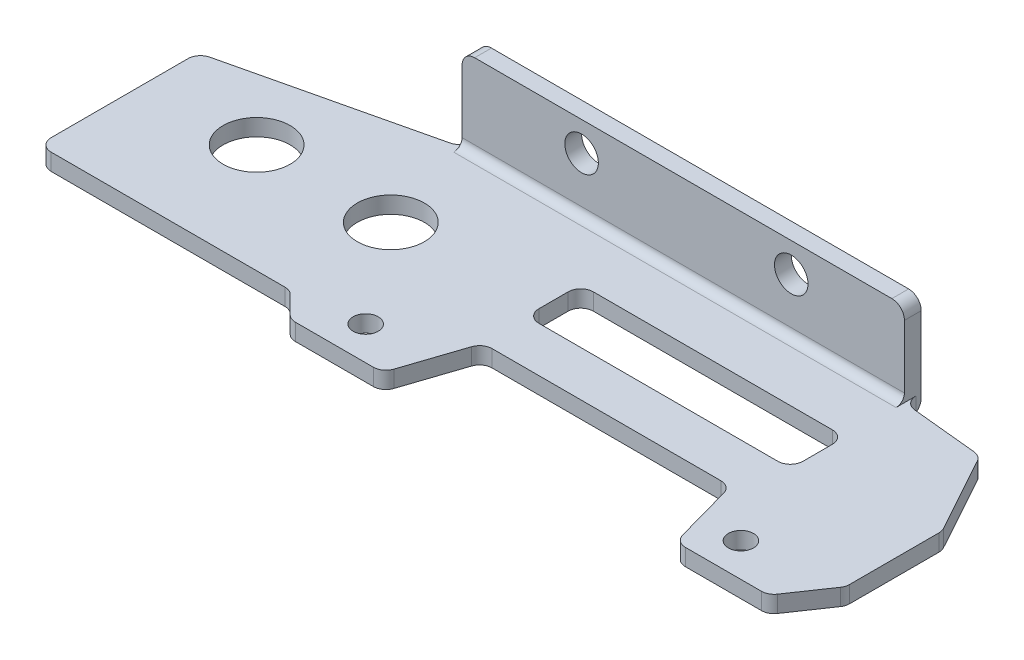
SolidWorks part; units mm, degrees
material "1060 Alloy"
ref_plane "Front Plane" through (0, 0, 0) normal (0, 0, 1) x (1, 0, 0)
ref_plane "Top Plane" through (0, 0, 0) normal (0, 1, 0) x (1, 0, 0)
ref_plane "Right Plane" through (0, 0, 0) normal (1, 0, 0) x (0, 0, -1)
sketch "Sketch1" plane through (0, 0, 0) normal (0, 1, 0) x (1, 0, 0)
  line L0 (0, 5.6) -> (30, 5.6)
  line L1 (33, 2.6) -> (44, 2.6)
  line L2 (0, 5.6) -> (0, 24.6)
  line L3 (25.5, 32.6) -> (78.25, 32.6)
  line L4 (93.75, 8.1) -> (93.75, 19.6)
  line L5 (30, 5.6) -> (33, 2.6)
  line L6 (0, 24.6) -> (25.5, 30.6)
  line L7 (25.5, 30.6) -> (25.5, 32.6)
  line L8 (78.25, 32.6) -> (78.25, 30.6)
  line L9 (78.25, 30.6) -> (88.25, 29.6)
  line L10 (88.25, 29.6) -> (93.75, 19.6)
  line L11 (93.75, 8.1) -> (90, 2.6)
  line L12 (44, 2.6) -> (47, 11.6)
  line L13 (47, 11.6) -> (76.5, 11.6)
  line L14 (76.5, 11.6) -> (79, 2.6)
  line L15 (79, 2.6) -> (90, 2.6)
  line L17 (46.75, 23.5) -> (78.25, 23.5)
  line L18 (46.75, 23.5) -> (46.75, 17)
  line L19 (46.75, 17) -> (78.25, 17)
  line L20 (78.25, 23.5) -> (78.25, 17)
  circle A0 centre (82.75, 6.6) radius 1.5
  circle A1 centre (38, 6.6) radius 1.5
  circle A2 centre (13, 18.6) radius 4
  circle A3 centre (29, 18.6) radius 4
  dimension "D20" = 3
  dimension "D21" = 4
  dimension "D22" = 11
  dimension "D23" = 38
  dimension "D24" = 3
  dimension "D25" = 8
  dimension "D26" = 13
  dimension "D27" = 16
  dimension "D28" = 13
  dimension "D1" = 52.75
  dimension "D2" = 10
  dimension "D3" = 3
  dimension "D4" = 3
  dimension "D5" = 2
  dimension "D6" = 25.5
  dimension "D7" = 8
  dimension "D8" = 3
  dimension "D9" = 10
  dimension "D10" = 5.5
  dimension "D11" = 3.75
  dimension "D12" = 5.5
  dimension "D13" = 29.5
  dimension "D14" = 11
  dimension "D15" = 9
  dimension "D16" = 3
  dimension "D17" = 11
  dimension "D18" = 30
  dimension "D19" = 19
  dimension "D29" = 6.5
  dimension "D30" = 31.5
  dimension "D31" = 15.5
  dimension "D32" = 5.4
  dimension "D33" = 2
extrude "Boss-Extrude1" add sketch "Sketch1" along normal blind 2
sketch "Sketch2" plane through (0, 2, 0) normal (0, 1, 0) x (1, 0, 0)
  line L1 (25.5, 32.6) -> (78.25, 32.6)
  line L2 (25.5, 32.6) -> (25.5, 30.6)
  line L3 (25.5, 30.6) -> (78.25, 30.6)
  line L4 (78.25, 32.6) -> (78.25, 30.6)
extrude "Boss-Extrude2" add sketch "Sketch2" along normal blind 10
sketch "Sketch3" plane through (0, 0, -32.6) normal (0, 0, -1) x (-1, 0, 0)
  line L0 (-78.25, 12) -> (-78.25, 0) construction
  line L1 (-78.25, 12) -> (-25.5, 12) construction
  circle A0 centre (-64.75, 8.5) radius 2
  circle A1 centre (-39.75, 8.5) radius 2
  dimension "D1" = 4
  dimension "D2" = 13.5
  dimension "D3" = 25
  dimension "D4" = 3.5
extrude "Cut-Extrude1" cut sketch "Sketch3" against normal through all
fillet "Fillet1" radius 1.5 20 edges at (46.75, 1, -17) (46.75, 1, -23.5) (0, 1, -24.6) (25.5, 1, -30.6) (25.5, 12, -31.6) (78.25, 1, -17) (78.25, 1, -23.5) (0, 1, -5.6) (30, 1, -5.6) (33, 1, -2.6) (44, 1, -2.6) (47, 1, -11.6) (76.5, 1, -11.6) (79, 1, -2.6) (90, 1, -2.6) (93.75, 1, -8.1) (93.75, 1, -19.6) (88.25, 1, -29.6) (78.25, 1, -30.6) (78.25, 12, -31.6)
fillet "Fillet2" radius 1 1 edges at (51.875, 2, -30.6)
fillet "Fillet3" radius 1.5 1 edges at (51.875, 0, -32.6)
ref_plane "Plane1" through (0, -10, 0) normal (0, -1, 0) x (-1, 0, 0)
